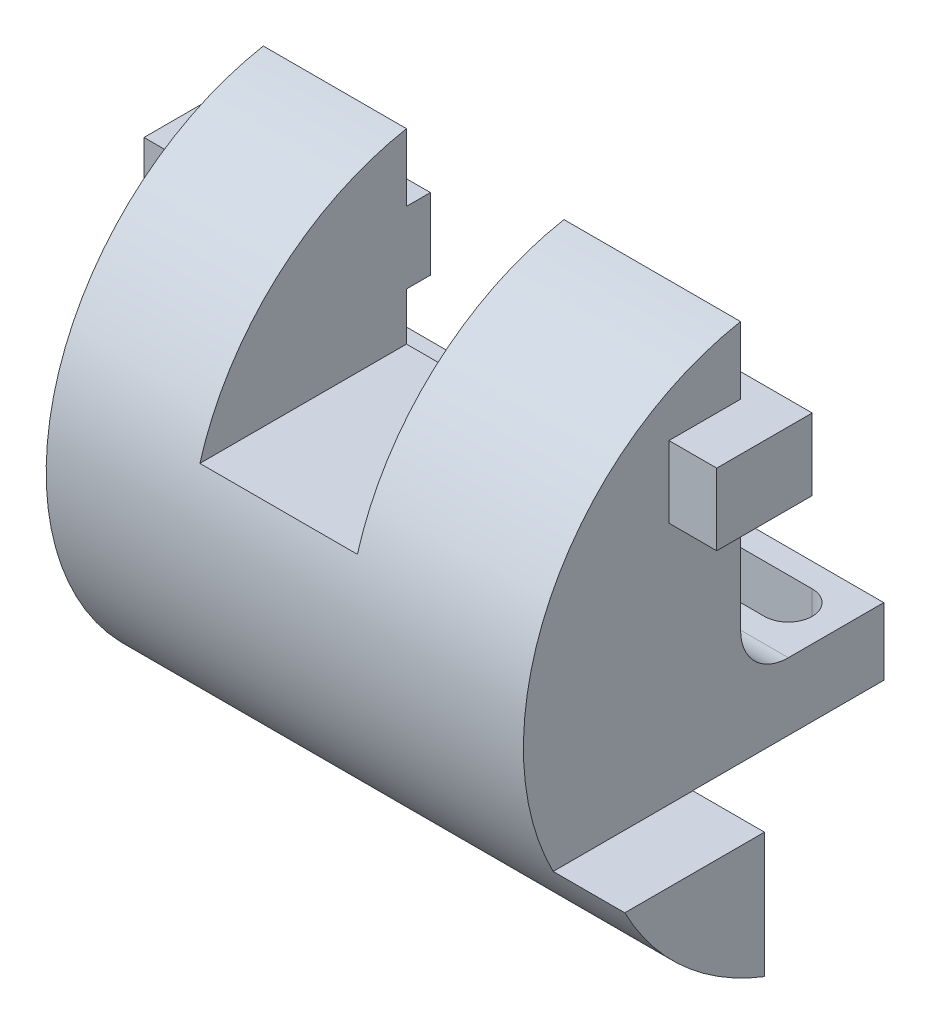
SolidWorks part; units mm, degrees
material "1060 Alloy"
ref_plane "Front Plane" through (0, 0, 0) normal (0, 0, 1) x (1, 0, 0)
ref_plane "Top Plane" through (0, 0, 0) normal (0, 1, 0) x (1, 0, 0)
ref_plane "Right Plane" through (0, 0, 0) normal (1, 0, 0) x (0, 0, -1)
sketch "Sketch3" plane through (0, 0, 0) normal (1, 0, 0) x (0, 0, -1)
  line L0 (0, -0.8989) -> (0, -47.819) construction
  line L1 (-44.557, -3.3887) -> (49.1139, -3.3887) construction
  line L2 (20, -35.7673) -> (20, -49.8722)
  line L3 (20, -35.7673) -> (0, -35.7673)
  line L6 (-10, -25.7673) -> (-10, 30.2327)
  line L7 (20, -49.8722) -> (-20, -49.8722)
  line L8 (-20, -49.8722) -> (-20, -76.1301)
  line L9 (20, -49.8722) -> (20, -44.8722) construction
  line L10 (20, -44.8722) -> (-55.3169, -28.8631) construction
  arc A0 (-10, 30.2327) -> (-20, -76.1301) centre (0, -24.359) ccw
  arc A1 (0, -35.7673) -> (-10, -25.7673) centre (0, -25.7673) cw
  dimension "D4" = 10
  dimension "D6" = 55.5
  dimension "D1" = 10
  dimension "D2" = 20
  dimension "D3" = 20
  dimension "D5" = 66
  dimension "D7" = 5
  dimension "D8" = 78
extrude "Boss-Extrude1" add sketch "Sketch3" along normal blind 115
sketch "Sketch4" plane through (115, 0, 0) normal (1, 0, 0) x (0, 0, -1)
  line L0 (-65.4024, 30.2327) -> (45.4024, 30.2327)
  line L3 (-65.4024, 30.2327) -> (-65.4024, -49.9185)
  line L4 (-65.4024, -49.9185) -> (45.4024, -49.9185)
  line L5 (45.4024, 30.2327) -> (45.4024, -49.9185)
  point P1 (-10, 30.2327)
extrude "Cut-Extrude1" cut sketch "Sketch4" against normal blind 15
ref_plane "Plane1" through (0, 31.141, 0) normal (0, 1, 0) x (1, 0, 0)
sketch "Sketch6" plane through (0, 31.141, 0) normal (0, 1, 0) x (1, 0, 0)
  line L0 (100, -10) -> (0, -10) construction
  line L1 (30, -10) -> (63, -10)
  line L2 (30, -10) -> (30, -55.5)
  line L3 (30, -55.5) -> (63, -55.5)
  line L4 (63, -10) -> (63, -55.5)
  line L5 (0, -55.5) -> (100, -55.5) construction
  dimension "D1" = 30
  dimension "D2" = 33
extrude "Cut-Extrude2" cut sketch "Sketch6" against normal blind 40
ref_plane "Plane2" through (0, 31.141, 0) normal (0, 1, 0) x (1, 0, 0)
sketch "Sketch9" plane through (0, -35.7673, 0) normal (0, 1, 0) x (1, 0, 0)
  line L0 (90, 10) -> (10, 10) construction
  line L1 (90, 5) -> (10, 5)
  line L2 (90, 15) -> (10, 15)
  arc A0 (90, 5) -> (90, 15) centre (90, 10) ccw
  arc A1 (10, 15) -> (10, 5) centre (10, 10) ccw
  point P2 (50, 10)
  dimension "D4" = 5
  dimension "D1" = 10
  dimension "D2" = 80
  dimension "D3" = 10
extrude "Cut-Extrude3" cut sketch "Sketch9" against normal through all
ref_plane "Plane3" through (0, 1.141, 0) normal (0, 1, 0) x (1, 0, 0)
sketch "Sketch10" plane through (0, 1.141, 0) normal (0, 1, 0) x (1, 0, 0)
  line L0 (63, -10) -> (63, -53.2917) construction
  line L1 (63, -25) -> (110, -25)
  line L2 (63, -25) -> (63, -5)
  line L3 (63, -5) -> (110, -5)
  line L4 (110, -25) -> (110, -5)
  line L5 (30, -10) -> (30, -53.2917) construction
  line L6 (30, -25) -> (-10, -25)
  line L7 (30, -25) -> (30, -5)
  line L8 (30, -5) -> (-10, -5)
  line L9 (-10, -25) -> (-10, -5)
  line L10 (100, -55.5) -> (100, -10) construction
  line L11 (100, -10) -> (63, -10) construction
  line L12 (100, -10) -> (0, -10) construction
  line L13 (0, -10) -> (0, -55.5) construction
  dimension "D1" = 10
  dimension "D2" = 5
  dimension "D3" = 20
  dimension "D4" = 5
  dimension "D5" = 20
  dimension "D6" = 10
extrude "Boss-Extrude2" add sketch "Sketch10" along normal blind 15
equation "\"A\"= 55.50"
equation "\"B\"= 66.00"
equation "\"C\"= 33.00"
